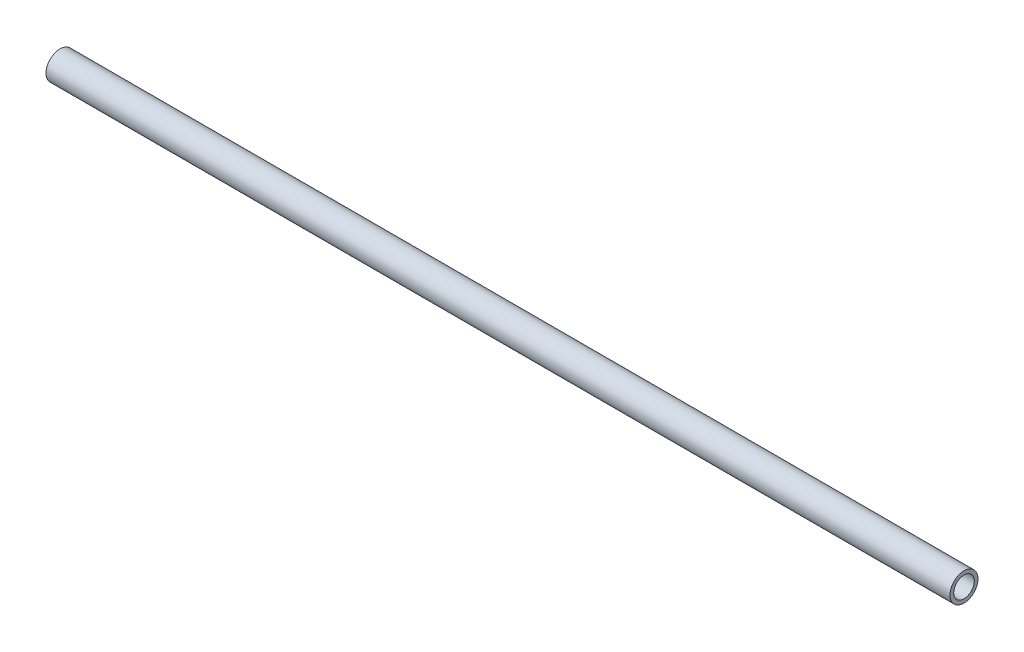
SolidWorks part; units mm, degrees
ref_plane "Front Plane" through (0, 0, 0) normal (0, 0, 1) x (1, 0, 0)
ref_plane "Top Plane" through (0, 0, 0) normal (0, 1, 0) x (1, 0, 0)
ref_plane "Right Plane" through (0, 0, 0) normal (1, 0, 0) x (0, 0, -1)
sketch "Axial profile (mm)" plane through (0, 0, 0) normal (0, 0, 1) x (1, 0, 0)
  line L0 (-110, 0) -> (75, 0) construction
  line L1 (13.7, 1.65) -> (158.7, 1.65)
  line L2 (158.7, 1.65) -> (158.7, 2.25)
  line L3 (158.7, 2.25) -> (13.7, 2.25)
  line L4 (13.7, 2.25) -> (13.7, 1.65)
revolve "Full revolution" add sketch "Axial profile (mm)" angle 360 about L0
